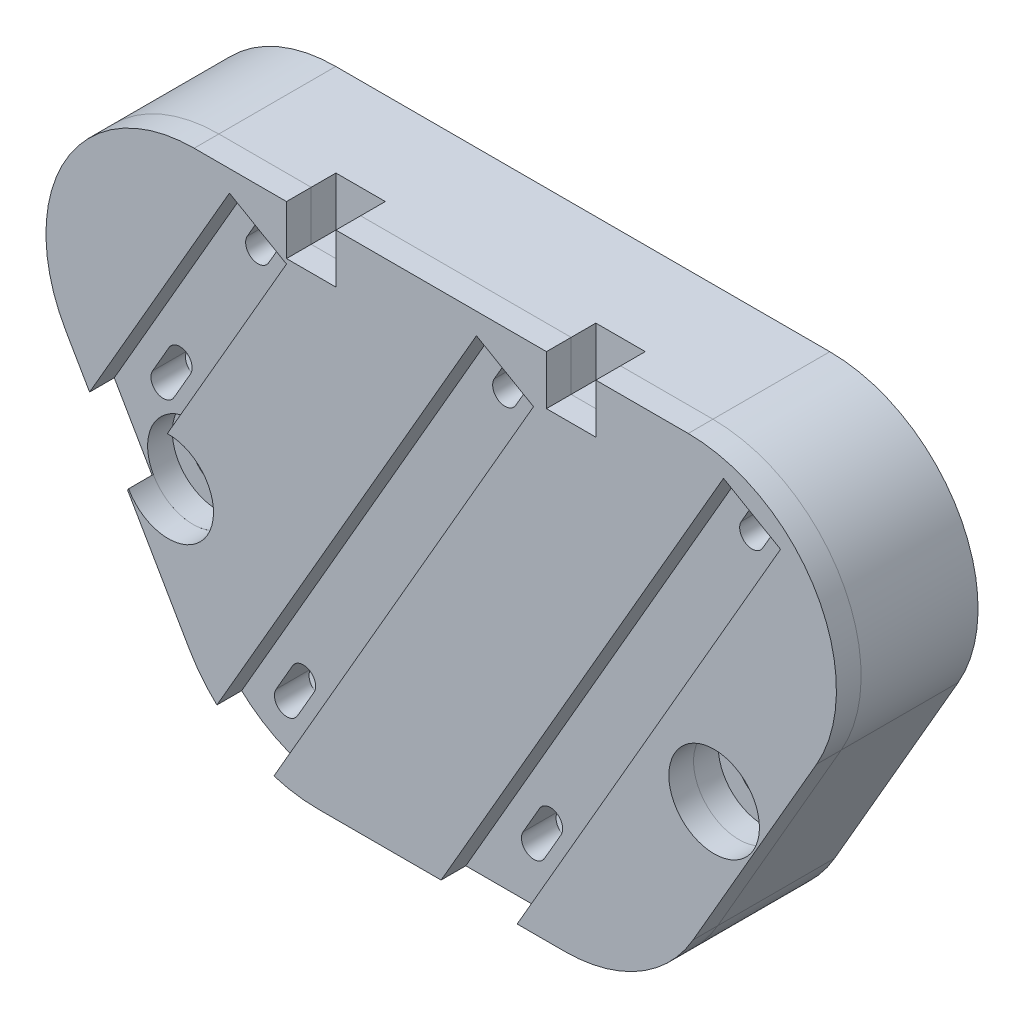
SolidWorks part; units mm, degrees
ref_plane "Front Plane" through (0, 0, 0) normal (0, 0, 1) x (1, 0, 0)
ref_plane "Top Plane" through (0, 0, 0) normal (0, 1, 0) x (1, 0, 0)
ref_plane "Right Plane" through (0, 0, 0) normal (1, 0, 0) x (0, 0, -1)
sketch "Sketch1" plane through (0, 0, 0) normal (0, 0, 1) x (1, 0, 0)
  line L0 (0, 9) -> (-30, 9)
  line L1 (0.2942, -17.4904) -> (7.7942, -4.5)
  line L2 (-7.5, -21.9904) -> (-22.5, -21.9904)
  line L3 (-30.2942, -17.4904) -> (-37.7942, -4.5)
  line L4 (-31.4462, -9.4952) -> (-32.7452, -10.2452) construction
  line L5 (-32.7452, -10.2452) -> (-34.0442, -10.9952) construction
  line L6 (-30.8971, -7.4462) -> (-29.3971, -10.0442) construction
  line L10 (-31.4462, -9.4952) -> (-30.1471, -8.7452) construction
  circle A0 centre (-22.5, -12.9904) radius 7.5
  circle A1 centre (-15, 0) radius 7.5
  circle A2 centre (0, 0) radius 7.5
  circle A3 centre (0, 0) radius 7.5
  circle A4 centre (-7.5, -12.9904) radius 7.5
  circle A5 centre (-30, 0) radius 7.5
  arc A6 (7.7942, -4.5) -> (0, 9) centre (0, 0) ccw
  arc A7 (-30, 9) -> (-37.7942, -4.5) centre (-30, 0) ccw
  arc A8 (-30.2942, -17.4904) -> (-22.5, -21.9904) centre (-22.5, -12.9904) ccw
  arc A9 (-7.5, -21.9904) -> (0.2942, -17.4904) centre (-7.5, -12.9904) ccw
  circle A10 centre (-30, 0) radius 9 construction
  circle A11 centre (-22.5, -12.9904) radius 9 construction
  circle A12 centre (-31.4462, -9.4952) radius 1.5 construction
  circle A13 centre (0, 0) radius 9 construction
  circle A14 centre (-7.5, -12.9904) radius 9 construction
  point P19 (-30.1858, -8.6795)
  point P35 (0, 0)
  point P37 (0, 0)
  point P39 (0, 0)
  point P40 (-30.12, -8.7912)
  point P41 (-31.4462, -9.5366)
  dimension "D2" = 15
  dimension "D3" = 1.5
  dimension "D4" = 1.5
  dimension "D5" = 3
  dimension "D1" = 0.25
extrude "Boss-Extrude1" add sketch "Sketch1" along normal blind 5 contours L2 A9 L1 A6 L0 A7 L3 A8 A5 A1 A3 A4 A0 | A5 A0 A1 | A4 A1 A0 | A4 A3 A1
sketch "Sketch2" plane through (0, 0, 5) normal (0, 0, 1) x (1, 0, 0)
  line L0 (-24.875, -17.104) -> (-22.5, -12.9904) construction
  line L1 (-22.5, -12.9904) -> (-15, 0) construction
  line L2 (-32.375, -4.1136) -> (-30, 0) construction
  line L3 (-30, 0) -> (-27.625, 4.1136) construction
  line L8 (-15, 0) -> (-12.625, 4.1136) construction
  line L9 (-9.875, -17.104) -> (-7.5, -12.9904) construction
  line L10 (0, 0) -> (-7.5, -12.9904) construction
  line L11 (-27.625, 4.1136) -> (-26.625, 5.8457) construction
  line L13 (0, 0) -> (2.375, 4.1136) construction
  line L15 (-28.2745, 4.4886) -> (-27.2745, 6.2207)
  line L16 (-26.9755, 3.7386) -> (-25.9755, 5.4707)
  line L17 (-32.375, -4.1136) -> (-33.375, -5.8457) construction
  line L19 (-31.7255, -4.4886) -> (-32.7255, -6.2207)
  line L20 (-33.0245, -3.7386) -> (-34.0245, -5.4707)
  line L22 (-24.875, -17.104) -> (-25.875, -18.8361) construction
  line L24 (-24.2255, -17.479) -> (-25.2255, -19.2111)
  line L25 (-25.5245, -16.729) -> (-26.5245, -18.4611)
  line L26 (-12.625, 4.1136) -> (-11.625, 5.8457) construction
  line L27 (-13.2745, 4.4886) -> (-12.2745, 6.2207)
  line L29 (-11.9755, 3.7386) -> (-10.9755, 5.4707)
  line L30 (-9.875, -17.104) -> (-10.875, -18.8361) construction
  line L31 (-9.2255, -17.479) -> (-10.2255, -19.2111)
  line L33 (-10.5245, -16.729) -> (-11.5245, -18.4611)
  line L34 (2.375, 4.1136) -> (3.375, 5.8457) construction
  line L35 (1.7255, 4.4886) -> (2.7255, 6.2207)
  line L37 (3.0245, 3.7386) -> (4.0245, 5.4707)
  line L42 (-22.5, -21.9904) -> (-7.5, -21.9904)
  line L43 (0.2942, -17.4904) -> (7.7942, -4.5)
  line L44 (0, 9) -> (-30, 9)
  line L45 (-37.7942, -4.5) -> (-30.2942, -17.4904)
  line L46 (-22.5, -21.9904) -> (-7.5, -21.9904)
  line L47 (0.2942, -17.4904) -> (7.7942, -4.5)
  line L48 (0, 9) -> (-30, 9)
  line L49 (-37.7942, -4.5) -> (-30.2942, -17.4904)
  arc A0 (-28.2745, 4.4886) -> (-26.9755, 3.7386) centre (-27.625, 4.1136) ccw
  arc A1 (-25.9755, 5.4707) -> (-27.2745, 6.2207) centre (-26.625, 5.8457) ccw
  arc A2 (-31.7255, -4.4886) -> (-33.0245, -3.7386) centre (-32.375, -4.1136) ccw
  arc A3 (-34.0245, -5.4707) -> (-32.7255, -6.2207) centre (-33.375, -5.8457) ccw
  arc A8 (-24.2255, -17.479) -> (-25.5245, -16.729) centre (-24.875, -17.104) ccw
  arc A9 (-26.5245, -18.4611) -> (-25.2255, -19.2111) centre (-25.875, -18.8361) ccw
  arc A10 (-13.2745, 4.4886) -> (-11.9755, 3.7386) centre (-12.625, 4.1136) ccw
  arc A11 (-10.9755, 5.4707) -> (-12.2745, 6.2207) centre (-11.625, 5.8457) ccw
  arc A12 (-9.2255, -17.479) -> (-10.5245, -16.729) centre (-9.875, -17.104) ccw
  arc A18 (-26.25, -6.4952) -> (-22.5, 0) centre (-30, 0) ccw construction
  arc A19 (-18.75, -6.4952) -> (-26.25, -6.4952) centre (-22.5, -12.9904) ccw construction
  arc A20 (-22.5, 0) -> (-18.75, -6.4952) centre (-15, 0) ccw construction
  arc A22 (-11.25, -6.4952) -> (-15, -12.9904) centre (-7.5, -12.9904) ccw construction
  arc A23 (-18.75, -6.4952) -> (-11.25, -6.4952) centre (-15, 0) ccw construction
  arc A24 (-15, -12.9904) -> (-18.75, -6.4952) centre (-22.5, -12.9904) ccw construction
  arc A26 (-3.75, -6.4952) -> (-11.25, -6.4952) centre (-7.5, -12.9904) ccw construction
  arc A27 (-7.5, 0) -> (-3.75, -6.4952) centre (0, 0) ccw construction
  arc A28 (-11.25, -6.4952) -> (-7.5, 0) centre (-15, 0) ccw construction
  arc A29 (-26.25, -6.4952) -> (-22.5, 0) centre (-30, 0) ccw construction
  arc A30 (-18.75, -6.4952) -> (-26.25, -6.4952) centre (-22.5, -12.9904) ccw construction
  arc A31 (-22.5, 0) -> (-18.75, -6.4952) centre (-15, 0) ccw construction
  arc A32 (-11.25, -6.4952) -> (-15, -12.9904) centre (-7.5, -12.9904) ccw construction
  arc A33 (-18.75, -6.4952) -> (-11.25, -6.4952) centre (-15, 0) ccw construction
  arc A34 (-15, -12.9904) -> (-18.75, -6.4952) centre (-22.5, -12.9904) ccw construction
  arc A35 (-3.75, -6.4952) -> (-11.25, -6.4952) centre (-7.5, -12.9904) ccw construction
  arc A36 (-7.5, 0) -> (-3.75, -6.4952) centre (0, 0) ccw construction
  arc A37 (-11.25, -6.4952) -> (-7.5, 0) centre (-15, 0) ccw construction
  arc A38 (-11.5245, -18.4611) -> (-10.2255, -19.2111) centre (-10.875, -18.8361) ccw
  arc A39 (1.7255, 4.4886) -> (3.0245, 3.7386) centre (2.375, 4.1136) ccw
  arc A40 (4.0245, 5.4707) -> (2.7255, 6.2207) centre (3.375, 5.8457) ccw
  circle A41 centre (-30, 0) radius 7.5 construction
  circle A42 centre (-22.5, -12.9904) radius 7.5 construction
  arc A47 (-7.5, -21.9904) -> (0.2942, -17.4904) centre (-7.5, -12.9904) ccw
  arc A48 (7.7942, -4.5) -> (0, 9) centre (0, 0) ccw
  arc A49 (-30, 9) -> (-37.7942, -4.5) centre (-30, 0) ccw
  arc A50 (-30.2942, -17.4904) -> (-22.5, -21.9904) centre (-22.5, -12.9904) ccw
  arc A51 (-7.5, -21.9904) -> (0.2942, -17.4904) centre (-7.5, -12.9904) ccw
  arc A52 (7.7942, -4.5) -> (0, 9) centre (0, 0) ccw
  arc A53 (-30, 9) -> (-37.7942, -4.5) centre (-30, 0) ccw
  arc A54 (-30.2942, -17.4904) -> (-22.5, -21.9904) centre (-22.5, -12.9904) ccw
  point P1 (0, 0)
  point P11 (-27.125, 4.9796)
  point P25 (-32.875, -4.9796)
  point P31 (-25.375, -17.97)
  point P37 (-12.125, 4.9796)
  point P43 (-10.375, -17.97)
  point P49 (2.875, 4.9796)
  point P55 (-26.25, 6.4952)
  point P58 (-26.25, -19.4856)
  point P61 (-33.75, -6.4952)
  point P76 (0, 0)
  point P77 (0, 0)
  point P78 (0, 0)
  point P79 (0, 0)
  point P80 (0, 0)
  point P82 (0, 0)
  point P83 (0, 0)
  point P84 (0, 0)
  dimension "D1" = 1.5
  dimension "D2" = 2
  dimension "D3" = 0
extrude "Boss-Extrude2" add sketch "Sketch2" along normal blind 2.1
sketch "Sketch3" plane through (0, 0, 7.1) normal (0, 0, 1) x (1, 0, 0)
  line L0 (-36.3509, -7) -> (-27.8571, 7.7117)
  line L2 (-27.8571, 7.7117) -> (-24.3929, 5.7117)
  line L3 (-34.0415, -11) -> (-24.3929, 5.7117)
  line L4 (-7.5, -21.9904) -> (-22.5, -21.9904) construction
  line L6 (-10.3868, -21.9904) -> (-7.5, -21.9904)
  line L8 (-22.5, -21.9904) -> (-7.5, -21.9904)
  line L9 (0.2942, -17.4904) -> (7.7942, -4.5)
  line L10 (0, 9) -> (-30, 9)
  line L11 (-37.7942, -4.5) -> (-30.2942, -17.4904)
  line L14 (-28.6195, -19.5897) -> (-12.8571, 7.7117)
  line L16 (-12.8571, 7.7117) -> (-9.3929, 5.7117)
  line L17 (-25.1554, -21.5897) -> (-9.3929, 5.7117)
  line L19 (-12.8571, 7.7117) -> (-25.1554, -21.5897) construction
  line L20 (-15.0056, -21.9904) -> (2.1429, 7.7117)
  line L22 (2.1429, 7.7117) -> (5.6071, 5.7117)
  line L23 (-10.3868, -21.9904) -> (5.6071, 5.7117)
  line L24 (-15.0056, -21.9904) -> (5.6071, 5.7117) construction
  line L26 (-32.875, -4.9796) -> (-27.125, 4.9796) construction
  line L27 (-25.375, -17.97) -> (-12.125, 4.9796) construction
  line L28 (-10.375, -17.97) -> (2.875, 4.9796) construction
  line L29 (-26.625, 5.8457) -> (-26.125, 6.7117) construction
  line L30 (-11.625, 5.8457) -> (-11.125, 6.7117) construction
  line L31 (3.375, 5.8457) -> (3.875, 6.7117) construction
  line L32 (-22.5, -21.9904) -> (-15.0056, -21.9904)
  line L33 (0.2942, -17.4904) -> (7.7942, -4.5)
  line L34 (0, 9) -> (-30, 9)
  line L35 (-37.7942, -4.5) -> (-30.2942, -17.4904)
  arc A1 (-25.1554, -21.5897) -> (-22.5, -21.9904) centre (-22.5, -12.9904) ccw
  arc A5 (-30.2942, -17.4904) -> (-22.5, -21.9904) centre (-22.5, -12.9904) ccw
  arc A6 (-7.5, -21.9904) -> (0.2942, -17.4904) centre (-7.5, -12.9904) ccw
  arc A7 (7.7942, -4.5) -> (0, 9) centre (0, 0) ccw
  arc A8 (-30, 9) -> (-37.7942, -4.5) centre (-30, 0) ccw
  arc A9 (-30.2942, -17.4904) -> (-28.6195, -19.5897) centre (-22.5, -12.9904) ccw
  arc A10 (-7.5, -21.9904) -> (0.2942, -17.4904) centre (-7.5, -12.9904) ccw
  arc A11 (7.7942, -4.5) -> (0, 9) centre (0, 0) ccw
  arc A12 (-30, 9) -> (-37.7942, -4.5) centre (-30, 0) ccw
  point P0 (2.875, 4.9796)
  point P1 (-22.0172, -14.1333)
  point P3 (-10.375, -17.97)
  point P5 (-12.125, 4.9796)
  point P8 (-25.375, -17.97)
  point P16 (-32.875, -4.9796)
  point P17 (-27.125, 4.9796)
  point P19 (0, 0)
  point P20 (-34.0442, -10.9952)
  point P21 (-34.0442, -10.9952)
  point P26 (-28.5316, -19.6702)
  point P29 (0, 0)
  point P44 (3.375, 5.8457)
  point P46 (-11.625, 5.8457)
  point P48 (-26.625, 5.8457)
  point P56 (-36.9873, -16.3719)
  point P62 (-34.5782, -11.9296)
  point P67 (0, 0)
  dimension "D2" = 1
  dimension "D3" = 4
  dimension "D1" = 0
extrude "Boss-Extrude3" add sketch "Sketch3" along normal blind 1.5
sketch "Sketch6" plane through (0, 0, 8.6) normal (0, 0, -1) x (-1, 0, 0)
  line L0 (0, 9) -> (30, 9) construction
  line L1 (5.6081, 9) -> (8.6081, 9)
  line L2 (5.6081, 9) -> (5.6081, 6)
  line L3 (5.6081, 6) -> (8.6081, 6)
  line L4 (8.6081, 9) -> (8.6081, 6)
  line L5 (30, 9) -> (0, 9) construction
  line L6 (21.3929, 9) -> (24.3929, 9)
  line L7 (21.3929, 9) -> (21.3929, 6)
  line L8 (21.3929, 6) -> (24.3929, 6)
  line L9 (24.3929, 9) -> (24.3929, 6)
  line L13 (30, 9) -> (0, 9) construction
  line L15 (15, 9) -> (15.0056, -21.9904) construction
  line L16 (21.3929, 6) -> (15.0005, 6) construction
  line L17 (8.6081, 6) -> (15.0005, 6) construction
  point P15 (0, 0)
  point P17 (24.2777, 6.7018)
  dimension "D1" = 3
  dimension "D2" = 3
extrude "Cut-Extrude1" cut sketch "Sketch6" along normal blind 3
sketch "Sketch7" plane through (0, 0, 8.6) normal (0, 0, 1) x (1, 0, 0)
  line L0 (-34.0442, -10.9952) -> (-32.6586, -10.1952) construction
  line L1 (-34.0415, -11) -> (-30.2942, -17.4904) construction
  line L2 (-32.6586, -10.1952) -> (-31.5761, -9.5702) construction
  line L3 (-31.5761, -9.5702) -> (-30.4935, -8.9452) construction
  line L4 (-31.4045, -7.3673) -> (-29.5825, -10.5231) construction
  line L5 (-15.0005, 9) -> (-15.0005, -21.9904) construction
  line L6 (-8.6081, 9) -> (-21.3929, 9) construction
  line L7 (-22.5, -21.9904) -> (-15.0056, -21.9904) construction
  line L8 (1.4034, -7.3673) -> (-0.4185, -10.5231) construction
  line L9 (1.575, -9.5702) -> (0.4924, -8.9452) construction
  line L10 (2.6575, -10.1952) -> (1.575, -9.5702) construction
  line L11 (4.0432, -10.9952) -> (2.6575, -10.1952) construction
  circle A0 centre (-31.5761, -9.5702) radius 1.25 construction
  arc A1 (-26.25, -6.4952) -> (-26.25, -19.4856) centre (-22.5, -12.9904) ccw construction
  arc A4 (-33.75, -6.4952) -> (-26.25, -6.4952) centre (-30, 0) ccw construction
  circle A5 centre (-31.5761, -9.5702) radius 2.75
  circle A6 centre (1.575, -9.5702) radius 1.25 construction
  circle A7 centre (1.575, -9.5702) radius 2.75
  point P9 (-30.4935, -8.9452)
  dimension "D1" = 2.5
  dimension "D3" = 5.5
  dimension "D2" = 1.6
extrude "Cut-Extrude5" cut sketch "Sketch7" against normal blind 3
sketch "Sketch8" plane through (0, 0, 5.6) normal (0, 0, 1) x (1, 0, 0)
  circle A0 centre (1.575, -9.5702) radius 2.75 construction
  circle A1 centre (-31.5761, -9.5702) radius 2.75 construction
  circle A2 centre (1.575, -9.5702) radius 2.75 construction
  circle A3 centre (-31.5761, -9.5702) radius 2.75 construction
  circle A4 centre (1.575, -9.5702) radius 1.55
  circle A5 centre (-31.5761, -9.5702) radius 1.55
  dimension "D1" = 3.1
extrude "Cut-Extrude6" cut sketch "Sketch8" against normal through all
equation "\"D2@Sketch7\"=1.50mm+.1"
equation "\"D1@Boss-Extrude2\"=1.5+.6"
